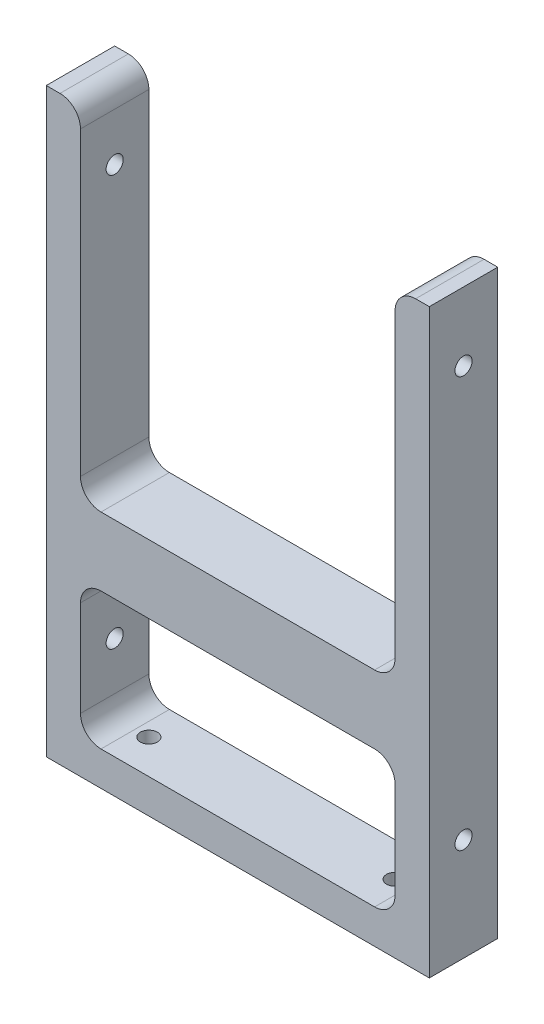
SolidWorks part; units mm, degrees
ref_plane "Спереди" through (0, 0, 0) normal (0, 0, 1) x (1, 0, 0)
ref_plane "Сверху" through (0, 0, 0) normal (0, 1, 0) x (1, 0, 0)
ref_plane "Справа" through (0, 0, 0) normal (1, 0, 0) x (0, 0, -1)
sketch "Эскиз1" plane through (0, 0, 0) normal (0, 0, 1) x (1, 0, 0)
  line L0 (-23, -17.5) -> (23, -17.5)
  line L1 (-28, 42.5) -> (-23, 42.5)
  line L2 (-28, 42.5) -> (-28, -42.5)
  line L3 (-28, -42.5) -> (28, -42.5)
  line L4 (28, 42.5) -> (28, -42.5)
  line L5 (-28, 42.5) -> (28, -42.5) construction
  line L6 (-28, -42.5) -> (28, 42.5) construction
  line L7 (23, 42.5) -> (28, 42.5)
  line L8 (-23, 42.5) -> (-23, -7.5)
  line L9 (-23, -37.5) -> (23, -37.5)
  line L10 (23, 42.5) -> (23, -7.5)
  line L13 (-23, -7.5) -> (23, -7.5)
  line L14 (-23, -17.5) -> (-23, -37.5)
  line L15 (23, -17.5) -> (23, -37.5)
  line L16 (-28, 0) -> (42.8015, 0) construction
  point P0 (0, 0)
  point P6 (0, 0)
  dimension "D1" = 56
  dimension "D2" = 85
  dimension "D3" = 5
  dimension "D4" = 5
  dimension "D5" = 10
  dimension "D6" = 20
  dimension "D7" = 5
extrude "Бобышка-Вытянуть1" add sketch "Эскиз1" along normal blind 10
fillet "Скругление1" radius 3 8 edges at (-23, -17.5, 5) (23, -17.5, 5) (23, -37.5, 5) (23, -7.5, 5) (23, 42.5, 5) (-23, -37.5, 5) (-23, -7.5, 5) (-23, 42.5, 5)
sketch "Эскиз2" plane through (0, -42.5, 0) normal (0, -1, 0) x (1, 0, 0)
  line L0 (-28, 5) -> (28, 5) construction
  line L1 (-28, 10) -> (-28, 0) construction
  line L2 (28, 10) -> (28, 0) construction
  line L3 (-18, 10) -> (-18, 0) construction
  line L4 (-28, 10) -> (28, 10) construction
  line L5 (-28, 0) -> (28, 0) construction
  line L6 (18, 10) -> (18, 0) construction
  dimension "D1" = 10
  dimension "D2" = 10
hole_wizard "Отверстие обработанное метчиком M3x0.51" positions "Эскиз4" profile "Эскиз3" tap size "M3x0.5" standard "Ansi Metric"
sketch "Эскиз4" plane through (0, -42.5, 0) normal (0, -1, 0) x (-1, 0, 0)
  line L0 (18, -10) -> (18, 0) construction
  line L1 (-18, -10) -> (-18, 0) construction
  point P0 (18, -5)
  point P4 (-18, -5)
sketch "Эскиз3" plane through (-18, -42.5, 5) normal (1, 0, 0) x (0, 0, -1)
  line L0 (0, 0) -> (0, 5)
  line L1 (0, 5) -> (1.25, 5)
  line L2 (1.25, 5) -> (1.25, 0)
  line L5 (1.25, 0) -> (0, 0)
  line L11 (0, -6.35) -> (0, 107.95) construction
  dimension "Диаметр проходного сверла" = 2.5
  dimension "Глубина проходного сверла" = 5
cosmetic thread "Отверстие резьбы1" parameters "D2"=3
cosmetic thread "Отверстие резьбы2" parameters "D2"=3
sketch "Эскиз5" plane through (28, 0, 0) normal (1, 0, 0) x (0, 0, -1)
  line L0 (-5, 42.5) -> (-5, -42.5) construction
  line L1 (-10, 42.5) -> (0, 42.5) construction
  line L2 (-10, -42.5) -> (0, -42.5) construction
  line L3 (0, 32.5) -> (-10, 32.5) construction
  line L4 (0, -42.5) -> (0, 42.5) construction
  line L5 (-10, -42.5) -> (-10, 42.5) construction
  line L6 (0, -27.5) -> (-10, -27.5) construction
  dimension "D1" = 15
  dimension "D2" = 10
  dimension "D3" = 60
hole_wizard "Отверстие обработанное метчиком M3x0.52" positions "Эскиз7" profile "Эскиз6" tap size "M3x0.5" standard "Ansi Metric" end condition through all
sketch "Эскиз7" plane through (28, 0, 0) normal (1, 0, 0) x (0, 0, -1)
  line L0 (0, 32.5) -> (-10, 32.5) construction
  line L1 (0, -27.5) -> (-10, -27.5) construction
  point P0 (-5, 32.5)
  point P4 (-5, -27.5)
sketch "Эскиз6" plane through (28, 32.5, 5) normal (0, 1, 0) x (0, 0, -1)
  line L0 (0, 0) -> (0, 56)
  line L1 (0, 56) -> (1.25, 56)
  line L2 (1.25, 56) -> (1.25, 0)
  line L5 (1.25, 0) -> (0, 0)
  line L11 (0, -6.35) -> (0, 107.95) construction
  dimension "Диаметр проходного сверла" = 2.5
  dimension "Глубина проходного сверла" = 56
cosmetic thread "Отверстие резьбы3" parameters "D2"=3
cosmetic thread "Отверстие резьбы4" parameters "D2"=3
